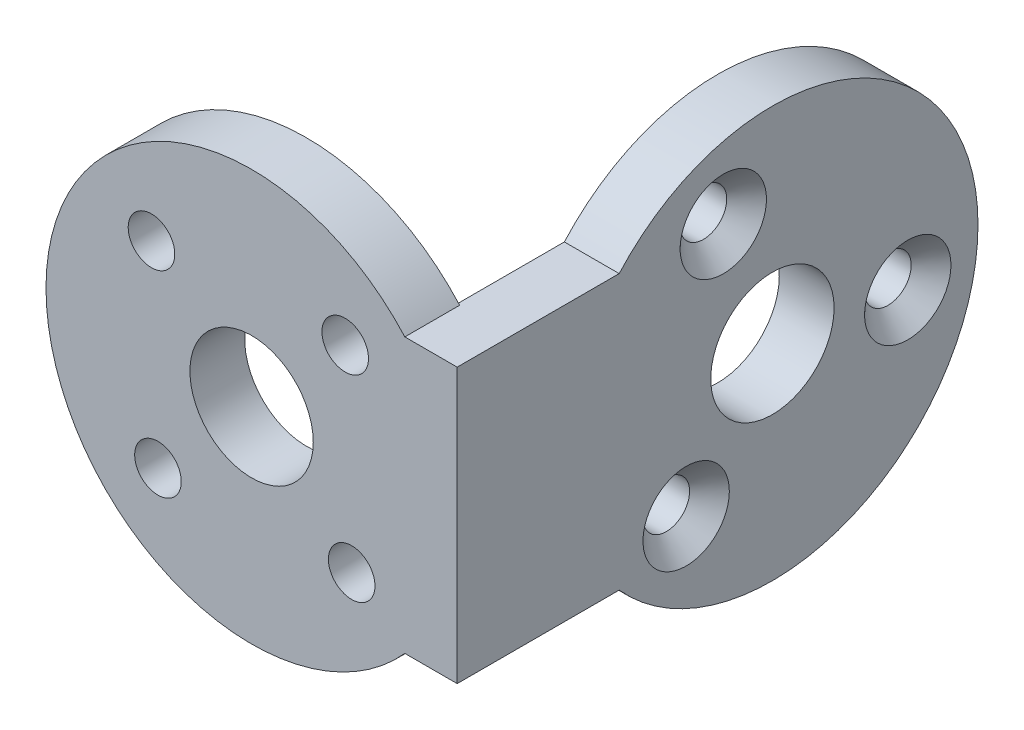
SolidWorks part; units mm, degrees
ref_plane "Plan de face" through (0, 0, 0) normal (0, 0, 1) x (1, 0, 0)
ref_plane "Plan de dessus" through (0, 0, 0) normal (0, 1, 0) x (1, 0, 0)
ref_plane "Plan de droite" through (0, 0, 0) normal (1, 0, 0) x (0, 0, -1)
sketch "Esquisse1" plane through (0, 0, 0) normal (0, 0, 1) x (1, 0, 0)
  line L0 (11.1803, 10) -> (15, 10)
  line L1 (11.1803, -10) -> (15, -10)
  line L2 (15, 10) -> (15, -10)
  arc A0 (11.1803, 10) -> (11.1803, -10) centre (0, 0) ccw
  circle A1 centre (0, 0) radius 4.5
  circle A2 centre (0, 0) radius 10 construction
  circle A3 centre (-7.3034, 6.8308) radius 1.5
  circle A4 centre (6.8308, 7.3034) radius 1.5
  circle A5 centre (7.3034, -6.8308) radius 1.5
  circle A6 centre (-6.8308, -7.3034) radius 1.5
  point P19 (0, 0)
  dimension "D2" = 20
  dimension "D3" = 3
  dimension "D4" = 9
  dimension "D5" = 30
  dimension "D6" = 15
  dimension "D7" = 20
  dimension "D1" = 4
extrude "Boss.-Extru.1" add sketch "Esquisse1" along normal blind 4
sketch "Esquisse3" plane through (15, 0, 0) normal (1, 0, 0) x (0, 0, -1)
  line L0 (0, 10) -> (7.8197, 10)
  line L1 (0, 0) -> (19, 0) construction
  line L2 (0, -10) -> (7.8197, -10)
  line L3 (0, 10) -> (0, -10)
  arc A0 (7.8197, 10) -> (7.8197, -10) centre (19, 0) cw
  circle A1 centre (19, 0) radius 4.5
  circle A2 centre (19, 0) radius 10 construction
  circle A3 centre (15.4163, 9.3358) radius 1.5001
  circle A5 centre (19, 0) radius 10 construction
  circle A7 centre (19, 0) radius 10 construction
  circle A9 centre (19, 0) radius 10 construction
  circle A10 centre (22.5837, -9.3358) radius 1.5001 [skipped]
  circle A11 centre (28.3358, 3.5837) radius 1.5001 [skipped]
  circle A12 centre (9.6642, -3.5837) radius 1.5001 [skipped]
  circle A13 centre (28.8769, -1.5643) radius 1.5001
  circle A14 centre (12.7068, -7.7715) radius 1.5001
  point P22 (19, 0)
  point P25 (19, 0)
  dimension "D1" = 30
  dimension "D2" = 4
  dimension "D3" = 20
  dimension "D4" = 9
  dimension "D5" = 3
  dimension "D6" = 19
extrude "Boss.-Extru.2" add sketch "Esquisse3" against normal blind 4
hole_wizard "Fraisage pour vis à tête fraisée M31" positions "Esquisse4" profile "Esquisse5" countersink size "M3" standard "Ansi Metric" end condition through all
sketch "Esquisse4" plane through (0, 0, 0) normal (0, 0, -1) x (-1, 0, 0)
  point P0 (-6.8308, 7.3034)
  point P3 (7.3034, 6.8308)
  point P6 (6.8308, -7.3034)
  point P9 (-7.3034, -6.8308)
sketch "Esquisse5" plane through (6.8308, 7.3034, 0) normal (1, 0, 0) x (0, 1, 0)
  line L0 (0, 0) -> (0, 4)
  line L1 (0, 4) -> (1.7, 4)
  line L2 (1.7, 4) -> (1.7, 1.45)
  line L3 (1.7, 1.45) -> (3.15, 0)
  line L5 (3.15, 0) -> (0, 0)
  line L6 (-1.7, 1.45) -> (-3.15, 0) construction
  line L11 (0, -6.35) -> (0, 107.95) construction
  dimension "Diamètre du perçage jusqu'au prochain" = 3.4
  dimension "Profondeur du perçage jusqu'au prochain" = 4
  dimension "Diamètre du fraisage entrant" = 6.3
  dimension "Angle du fraisage entrant" = 90
hole_wizard "Fraisage pour vis à tête fraisée M32" positions "Esquisse6" profile "Esquisse7" countersink size "M3" standard "Ansi Metric" end condition through all
sketch "Esquisse6" plane through (15, 0, 0) normal (1, 0, 0) x (0, 0, -1)
  point P0 (15.4163, 9.3358)
  point P3 (28.8769, -1.5643)
  point P6 (12.7068, -7.7715)
sketch "Esquisse7" plane through (15, 9.3358, -15.4163) normal (0, 1, 0) x (0, 0, -1)
  line L0 (0, 0) -> (0, 30)
  line L1 (0, 30) -> (1.7, 30)
  line L2 (1.7, 30) -> (1.7, 1.45)
  line L3 (1.7, 1.45) -> (3.15, 0)
  line L5 (3.15, 0) -> (0, 0)
  line L6 (-1.7, 1.45) -> (-3.15, 0) construction
  line L11 (0, -6.35) -> (0, 107.95) construction
  dimension "Diamètre du perçage jusqu'au prochain" = 3.4
  dimension "Profondeur du perçage jusqu'au prochain" = 30
  dimension "Diamètre du fraisage entrant" = 6.3
  dimension "Angle du fraisage entrant" = 90
